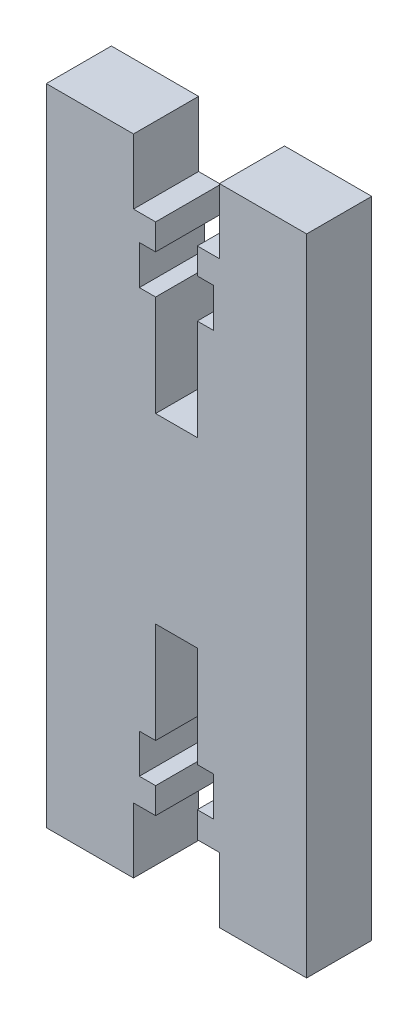
SolidWorks part; units mm, degrees
ref_plane "Plan de face" through (0, 0, 0) normal (0, 0, 1) x (1, 0, 0)
ref_plane "Plan de dessus" through (0, 0, 0) normal (0, 1, 0) x (1, 0, 0)
ref_plane "Plan de droite" through (0, 0, 0) normal (1, 0, 0) x (0, 0, -1)
sketch "Esquisse1" plane through (0, 0, 0) normal (0, 0, 1) x (1, 0, 0)
  line L0 (-12.9111, 41.3251) -> (-12.9111, -8.1749)
  line L1 (-12.9111, -8.1749) -> (-6.2111, -8.1749)
  line L2 (-6.2111, -8.1749) -> (-6.2111, -3.1749)
  line L3 (-6.2111, -3.1749) -> (-4.5111, -3.1749)
  line L4 (-4.5111, -3.1749) -> (-4.5111, -1.1782)
  line L5 (-4.5111, -1.1782) -> (-5.7611, -1.1782)
  line L6 (-5.7611, -1.1782) -> (-5.7611, 1.8218)
  line L7 (-5.7611, 1.8218) -> (-4.5111, 1.8218)
  line L8 (-4.5111, 1.8218) -> (-4.5111, 9.5751)
  line L9 (-4.5111, 9.5751) -> (-1.3111, 9.5751)
  line L10 (-1.3111, 9.5751) -> (-1.3111, 1.8218)
  line L11 (-1.3111, 1.8218) -> (-0.0611, 1.8218)
  line L12 (-0.0611, 1.8218) -> (-0.0611, -1.1782)
  line L13 (-0.0611, -1.1782) -> (-1.3111, -1.1782)
  line L14 (-1.3111, -1.1782) -> (-1.3111, -3.1749)
  line L15 (-1.3111, -3.1749) -> (0.3889, -3.1749)
  line L16 (0.3889, -3.1749) -> (0.3889, -8.1749)
  line L17 (0.3889, -8.1749) -> (7.0889, -8.1749)
  line L18 (7.0889, -8.1749) -> (7.0889, 41.3251)
  line L19 (-12.9111, 9.5751) -> (7.0889, 9.5751) construction
  line L20 (-12.9111, 16.5751) -> (7.0889, 16.5751) construction
  line L21 (-12.9111, 23.5751) -> (7.0889, 23.5751) construction
  line L22 (0.3889, 41.3251) -> (7.0889, 41.3251)
  line L23 (0.3889, 36.3251) -> (0.3889, 41.3251)
  line L24 (-1.3111, 36.3251) -> (0.3889, 36.3251)
  line L25 (-1.3111, 34.3284) -> (-1.3111, 36.3251)
  line L26 (-0.0611, 34.3284) -> (-1.3111, 34.3284)
  line L27 (-0.0611, 31.3284) -> (-0.0611, 34.3284)
  line L28 (-1.3111, 31.3284) -> (-0.0611, 31.3284)
  line L29 (-1.3111, 23.5751) -> (-1.3111, 31.3284)
  line L30 (-4.5111, 23.5751) -> (-1.3111, 23.5751)
  line L31 (-4.5111, 31.3284) -> (-4.5111, 23.5751)
  line L32 (-5.7611, 31.3284) -> (-4.5111, 31.3284)
  line L33 (-5.7611, 34.3284) -> (-5.7611, 31.3284)
  line L34 (-4.5111, 34.3284) -> (-5.7611, 34.3284)
  line L35 (-4.5111, 36.3251) -> (-4.5111, 34.3284)
  line L36 (-6.2111, 36.3251) -> (-4.5111, 36.3251)
  line L37 (-6.2111, 41.3251) -> (-6.2111, 36.3251)
  line L38 (-12.9111, 41.3251) -> (-6.2111, 41.3251)
  dimension "D1" = 24.75
  dimension "D2" = 24.75
  dimension "D3" = 20
  dimension "D4" = 6.7
  dimension "D5" = 6.7
  dimension "D6" = 3.2
  dimension "D7" = 1.7
  dimension "D8" = 7
  dimension "D9" = 3.2
  dimension "D10" = 0
  dimension "D11" = 5.7
  dimension "D12" = 1.25
  dimension "D13" = 1.9967
  dimension "D14" = 1.9967
  dimension "D15" = 3
  dimension "D16" = 3
  dimension "D17" = 5
  dimension "D18" = 5
extrude "Boss.-Extru.1" add sketch "Esquisse1" along normal blind 5
